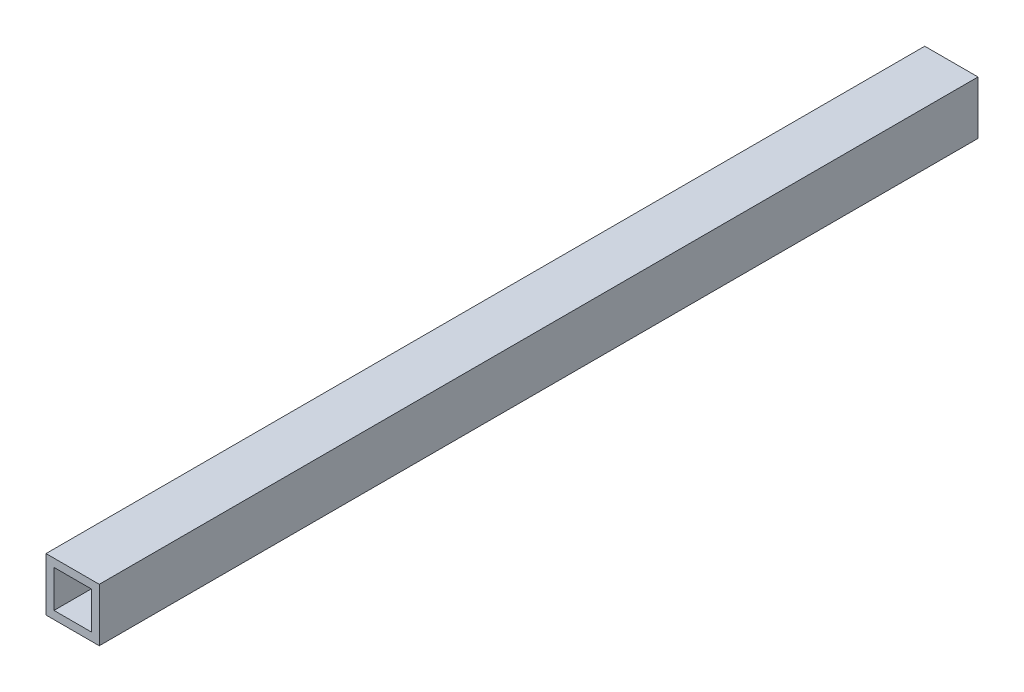
SolidWorks part; units mm, degrees
ref_plane "前视基准面" through (0, 0, 0) normal (0, 0, 1) x (1, 0, 0)
ref_plane "上视基准面" through (0, 0, 0) normal (0, 1, 0) x (1, 0, 0)
ref_plane "右视基准面" through (0, 0, 0) normal (1, 0, 0) x (0, 0, -1)
other "Configuration Table"
sketch "草图1" plane through (0, 0, 0) normal (0, 0, 1) x (1, 0, 0)
  line L1 (-5, 5) -> (5, 5)
  line L2 (-5, 5) -> (-5, -5)
  line L3 (-5, -5) -> (5, -5)
  line L4 (5, 5) -> (5, -5)
  line L5 (-5, 5) -> (5, -5) construction
  line L6 (-5, -5) -> (5, 5) construction
  line L7 (-3.5, 3.5) -> (3.5, 3.5)
  line L8 (-3.5, 3.5) -> (-3.5, -3.5)
  line L9 (-3.5, -3.5) -> (3.5, -3.5)
  line L10 (3.5, 3.5) -> (3.5, -3.5)
  line L11 (-3.5, 3.5) -> (3.5, -3.5) construction
  line L12 (-3.5, -3.5) -> (3.5, 3.5) construction
  point P0 (0, 0)
  point P5 (0, 0)
  dimension "D1" = 10
  dimension "D2" = 1.5
  dimension "D3" = 10
extrude "凸台-拉伸1" add sketch "草图1" along normal blind 165
